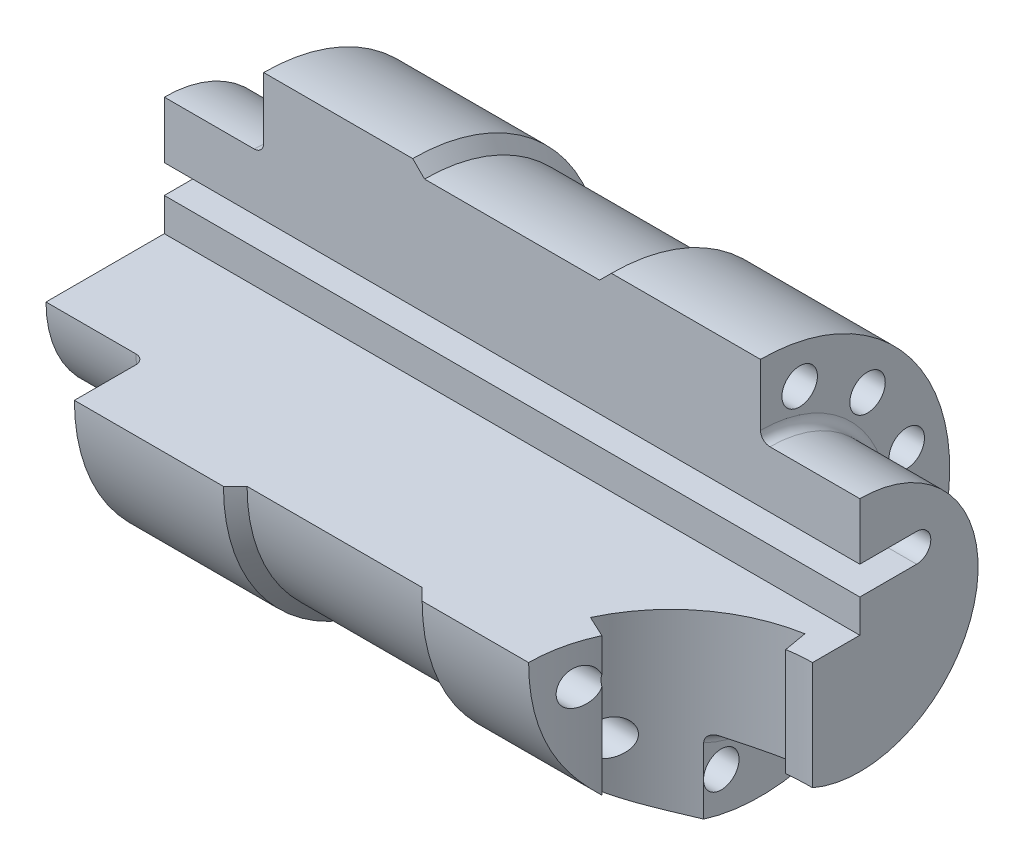
SolidWorks part; units mm, degrees
material "AISI 1020"
ref_plane "Plan de face" through (0, 0, 0) normal (0, 0, 1) x (1, 0, 0)
ref_plane "Plan de dessus" through (0, 0, 0) normal (0, 1, 0) x (1, 0, 0)
ref_plane "Plan de droite" through (0, 0, 0) normal (1, 0, 0) x (0, 0, -1)
sketch "Esquisse1" plane through (0, 0, 0) normal (0, 0, 1) x (1, 0, 0)
  line L0 (0, 0) -> (-117.7281, 0)
  line L1 (-117.7281, 0) -> (-117.7281, 25)
  line L2 (-117.7281, 25) -> (-96.7281, 25)
  line L3 (-96.7281, 25) -> (-96.7281, 40)
  line L4 (-96.7281, 40) -> (-65.2281, 40)
  line L5 (-65.2281, 40) -> (-62.7281, 37.5)
  line L6 (-62.7281, 37.5) -> (-25.7281, 37.5)
  line L7 (-25.7281, 37.5) -> (-23.2281, 40)
  line L8 (-23.2281, 40) -> (8.2719, 40)
  line L9 (8.2719, 40) -> (8.2719, 25)
  line L10 (8.2719, 25) -> (29.2719, 25)
  line L11 (29.2719, 25) -> (29.2719, 0)
  line L12 (29.2719, 0) -> (0, 0)
  line L13 (-65.2281, 40) -> (-65.2281, 30.1665) construction
  line L14 (-23.2281, 40) -> (-23.2281, 23.5403) construction
  dimension "D1" = 40
  dimension "D2" = 25
  dimension "D3" = 25
  dimension "D4" = 40
  dimension "D5" = 147
  dimension "D6" = 45
  dimension "D7" = 45
  dimension "D8" = 2.5
  dimension "D9" = 31.5
  dimension "D10" = 21
revolve "Révolution1" add sketch "Esquisse1" angle 270 about L0
sketch "Esquisse3" plane through (-117.7281, 0, 0) normal (-1, 0, 0) x (0, 0, 1)
  line L0 (-12, 10) -> (0, 10) construction
  line L1 (0, 25) -> (0, 0) construction
  line L2 (-12, 13) -> (0, 13)
  line L3 (-12, 7) -> (0, 7)
  arc A0 (-12, 13) -> (-12, 7) centre (-12, 10) ccw
  arc A1 (0, 7) -> (0, 13) centre (0, 10) ccw
  point P4 (-6, 10)
  dimension "D2" = 3
  dimension "D1" = 7
  dimension "D3" = 12
extrude "Enlèv. mat.-Extru.1" cut sketch "Esquisse3" against normal through all both and the other way through all
fillet "Congé1" radius 2 2 edges at (8.2719, -17.6777, -17.6777) (-96.7281, -17.6777, -17.6777)
sketch "Esquisse4" plane through (-117.7281, 0, 0) normal (-1, 0, 0) x (0, 0, 1)
  arc A0 (0, 25) -> (25, 0) centre (0, 0) ccw construction
  arc A1 (0, 40) -> (40, 0) centre (0, 0) ccw construction
  arc A2 (0, 25) -> (25, 0) centre (0, 0) ccw
  arc A3 (0, 40) -> (40, 0) centre (0, 0) ccw
sketch "Esquisse5" plane through (0, 0, 0) normal (0, 1, 0) x (1, 0, 0)
  line L12 (29.2719, 0) -> (-117.7281, 0)
  line L13 (-117.7281, 0) -> (-117.7281, -25)
  line L14 (-117.7281, -25) -> (-98.7281, -25)
  line L15 (-96.7281, -27) -> (-96.7281, -40)
  line L16 (-96.7281, -40) -> (-65.2281, -40)
  line L17 (-65.2281, -40) -> (-62.7281, -37.5)
  line L18 (-62.7281, -37.5) -> (-25.7281, -37.5)
  line L19 (-25.7281, -37.5) -> (-23.2281, -40)
  line L20 (-23.2281, -40) -> (8.2719, -40)
  line L21 (8.2719, -40) -> (8.2719, -27)
  line L22 (10.2719, -25) -> (29.2719, -25)
  line L23 (29.2719, -25) -> (29.2719, 0)
  line L24 (29.2719, 0) -> (-117.7281, 0)
  line L25 (-117.7281, 0) -> (-117.7281, -25)
  line L26 (-117.7281, -25) -> (-98.7281, -25)
  line L27 (-96.7281, -27) -> (-96.7281, -40)
  line L28 (-96.7281, -40) -> (-65.2281, -40)
  line L29 (-65.2281, -40) -> (-62.7281, -37.5)
  line L30 (-62.7281, -37.5) -> (-25.7281, -37.5)
  line L31 (-25.7281, -37.5) -> (-23.2281, -40)
  line L32 (-23.2281, -40) -> (8.2719, -40)
  line L33 (8.2719, -40) -> (8.2719, -27)
  line L34 (10.2719, -25) -> (29.2719, -25)
  line L35 (29.2719, -25) -> (29.2719, 0)
  arc A2 (-96.7281, -27) -> (-98.7281, -25) centre (-98.7281, -27) ccw
  arc A3 (10.2719, -25) -> (8.2719, -27) centre (10.2719, -27) ccw
  arc A4 (-96.7281, -27) -> (-98.7281, -25) centre (-98.7281, -27) ccw
  arc A5 (10.2719, -25) -> (8.2719, -27) centre (10.2719, -27) ccw
  dimension "D1" = 0
sketch "Esquisse6" plane through (-96.7281, 0, 0) normal (-1, 0, 0) x (0, 0, 1)
  line L0 (0, 40) -> (0, -43.1206)
  line L1 (40, 0) -> (-48.3199, 0)
  line L2 (-8.2822, 30.9096) -> (0, 0) construction
  circle A0 centre (0, 0) radius 32 construction
  circle A1 centre (-8.2822, 30.9096) radius 3.75
  point P13 (0, 0)
  dimension "D1" = 64
  dimension "D2" = 7.5
  dimension "D3" = 15
extrude "Enlèv. mat.-Extru.2" cut sketch "Esquisse6" against normal through all both and the other way through all contours A0 A1 | A0 A1
pattern_circular "Répétition circulaire1" [suppressed] count 9 every 33.75
sketch "Esquisse8" plane through (-117.7281, 0, 0) normal (-1, 0, 0) x (0, 0, 1)
  point P0 (0, 0)
sketch "Esquisse11" plane through (-117.7281, 0, 0) normal (-1, 0, 0) x (0, 0, 1)
  line L0 (0, -25) -> (0, 0)
  line L1 (0, 0) -> (-25, 0)
  arc A0 (0, 25) -> (25, 0) centre (0, 0) ccw construction
pattern_circular "Répétition circulaire2" count 12 every 30 about axis through (0, 0, 0) along (1, 0, 0) of "Enlèv. mat.-Extru.2"
sketch "Esquisse9" plane through (0, 0, 0) normal (0, 1, 0) x (1, 0, 0)
  line L0 (29.2719, -25) -> (29.2719, -40)
  line L1 (8.2719, -40) -> (29.2719, -40)
  line L2 (29.2719, -40) -> (-2.4488, -25.2084)
  line L3 (29.2719, -40) -> (23.1943, -5.5317)
  line L4 (-23.2281, -40) -> (8.2719, -40) construction
  line L5 (29.2719, -25) -> (29.2719, 0) construction
  arc A0 (23.1943, -5.5317) -> (-2.4488, -25.2084) centre (29.2719, -40) ccw
  circle A1 centre (29.2719, -40) radius 30
  line M14 (-23.2281, -40) -> (8.2719, -40)
  line M15 (8.2719, -40) -> (8.2719, -27)
  arc M16 (8.2719, -27) -> (10.2719, -25) centre (10.2719, -27) cw
  line M17 (10.2719, -25) -> (29.2719, -25)
  line M18 (29.2719, -25) -> (29.2719, 0)
  dimension "D1" = 60
  dimension "D2" = 70
  dimension "D3" = 25
  dimension "D4" = 10
extrude "Enlèv. mat.-Extru.3" cut sketch "Esquisse9" against normal through all both and the other way through all contours A1 L3 A0 L2 | A1 L0 L1 M14 M18 | L2 A1 M14 M15 | A1 L3 M18 M17 | L3 A1 L2 M15 M16 M17
sketch "Esquisse10" plane through (-117.7281, 0, 0) normal (-1, 0, 0) x (0, 0, 1)
  line L0 (-4.7763, 3) -> (-19.9086, 3)
  line L1 (-4.7763, 3) -> (-4.7763, -4)
  line L2 (-4.7763, -4) -> (18.9898, -4)
  line L3 (-12, 7) -> (0, 7) construction
  line L4 (25, 0) -> (0, 0) construction
  arc A0 (-19.9086, 3) -> (18.9898, -4) centre (-0.1614, 1.1557) ccw
  arc A2 (0, 25) -> (25, 0) centre (0, 0) ccw construction
  dimension "D3" = 4
  dimension "D1" = 4
  dimension "D2" = 4
extrude "Enlèv. mat.-Extru.4" cut sketch "Esquisse10" against normal blind 10 and the other way through all contours A0 L2 L1 L0
fillet "Congé2" radius 1 4 edges at (-107.7281, -0.5, -4.7763) (-107.7281, -4, 7.1068) (-107.7281, -18.3639, -3.6741) (-107.7281, 3, -12.3424)
fillet "Congé3" [suppressed] radius 1
equation "\"A\"= 147"
equation "\"B\"=21"
equation "\"C\"=31.5"
equation "\"D5@Esquisse1\"=\"A\""
equation "\"D9@Esquisse1\"=\"C\""
equation "\"D10@Esquisse1\"=\"B\""
